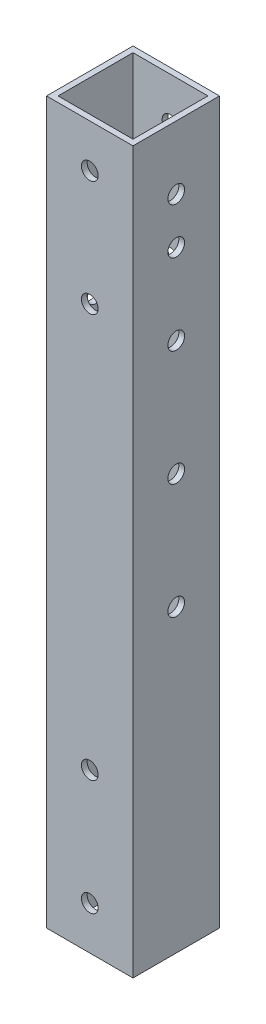
SolidWorks part; units mm, degrees
material "Thornel Mat VMA"
ref_plane "前视基准面" through (0, 0, 0) normal (0, 0, 1) x (1, 0, 0)
ref_plane "上视基准面" through (0, 0, 0) normal (0, 1, 0) x (1, 0, 0)
ref_plane "右视基准面" through (0, 0, 0) normal (1, 0, 0) x (0, 0, -1)
sketch "草图1" plane through (0, 0, 0) normal (0, 1, 0) x (1, 0, 0)
  line L1 (-7.5, -7.5) -> (7.5, -7.5)
  line L2 (-7.5, -7.5) -> (-7.5, 7.5)
  line L3 (-7.5, 7.5) -> (7.5, 7.5)
  line L4 (7.5, -7.5) -> (7.5, 7.5)
  line L5 (-7.5, -7.5) -> (7.5, 7.5) construction
  line L6 (-7.5, 7.5) -> (7.5, -7.5) construction
  point P0 (0, 0)
  dimension "D1" = 15
  dimension "D2" = 15
extrude "拉伸-薄壁1" add sketch "草图1" along normal blind 125 thin thin type one direction reverse wall 1
sketch "草图2" plane through (0, 0, 7.5) normal (0, 0, 1) x (1, 0, 0)
  line L0 (0, 0) -> (0, 125) construction
  line L1 (-7.5, 125) -> (7.5, 125) construction
  line L2 (-7.5, 0) -> (7.5, 0) construction
  line L3 (-1000, 62.5) -> (49000, 62.5) construction
  circle A0 centre (0, 7.5) radius 1.45
  circle A1 centre (0, 27.5) radius 1.45
  circle A2 centre (0, 97.5) radius 1.45
  circle A3 centre (0, 117.5) radius 1.45
  point P14 (0, 62.5)
  dimension "D1" = 2.9
  dimension "D2" = 7.5
  dimension "D3" = 20
extrude "切除-拉伸1" cut sketch "草图2" against normal through all
sketch "草图3" plane through (7.5, 0, 0) normal (1, 0, 0) x (0, 0, -1)
  line L0 (0, 0) -> (0, 125) construction
  line L1 (-7.5, 125) -> (7.5, 125) construction
  line L2 (-7.5, 0) -> (7.5, 0) construction
  circle A0 centre (0, 72) radius 1.45
  circle A1 centre (0, 92) radius 1.45
  circle A2 centre (0, 52) radius 1.45
  circle A3 centre (0, 114) radius 1.45
  circle A4 centre (0, 106) radius 1.45
  dimension "D4" = 2.9
  dimension "D5" = 11
  dimension "D6" = 8
  dimension "D1" = 20
  dimension "D2" = 20
  dimension "D3" = 72
extrude "切除-拉伸2" cut sketch "草图3" against normal through all
